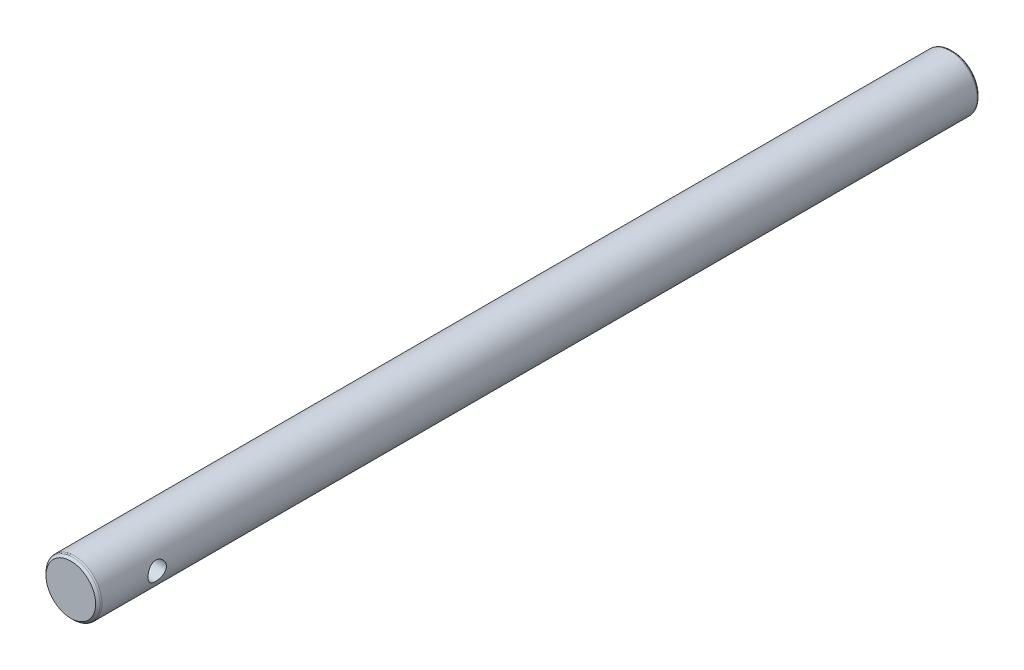
SolidWorks part; units mm, degrees
ref_plane "Front Plane" through (0, 0, 0) normal (0, 0, 1) x (1, 0, 0)
ref_plane "Top Plane" through (0, 0, 0) normal (0, 1, 0) x (1, 0, 0)
ref_plane "Right Plane" through (0, 0, 0) normal (1, 0, 0) x (0, 0, -1)
sketch "Sketch1" plane through (0, 0, 0) normal (0, 0, 1) x (1, 0, 0)
  line L0 (-4.7625, 0) -> (4.7625, 0) construction
  point P4 (0, 0)
  dimension "OD" = 9.525
sketch "Sketch2" plane through (0, 0, 0) normal (1, 0, 0) x (0, 0, -1)
  line L0 (152.4, 0) -> (-152.4, 0) construction
  line L1 (-152.4, 4.7625) -> (-152.4, -4.7625) construction
  line L2 (152.4, 4.7625) -> (152.4, -4.7625) construction
  point P0 (-141.4462, 0)
  point P4 (0, 0)
  point P6 (141.4462, 0)
  point P10 (152.4, 0)
  point P12 (-152.4, 0)
  dimension "Length" = 304.8
  dimension "D1" = 10.9537
  dimension "D2" = 10.9537
  dimension "D3" = 9.525
sketch "Sketch3" plane through (0, 0, 0) normal (0, 0, 1) x (1, 0, 0)
  circle A0 centre (0, 0) radius 4.7625
extrude "Boss-Extrude1" add sketch "Sketch3" along normal mid plane 152.4
chamfer "Chamfer1" distance 0.4763 angle 45 2 edges at (4.7625, 0, 76.2) (4.7625, 0, -76.2)
fillet "Fillet2" radius 0.3572 2 edges at (4.7625, 0, 75.7238) (4.7625, 0, -75.7237)
sketch "Sketch4" plane through (-4.7625, -167.656, -241.6273) normal (-1, 0, 0) x (0, 0, 1)
  line L0 (317.2031, 167.656) -> (-49682.7969, 167.656) construction
  line L1 (317.2031, 162.8935) -> (317.2031, 172.4185) construction
  line L2 (317.8273, 163.3698) -> (317.8273, 171.9423) construction
  circle A0 centre (307.6673, 167.656) radius 1.5875
  point P6 (317.2031, 167.656)
  point P7 (0, 0)
  dimension "D1" = 3.175
  dimension "D2" = 10.16
extrude "Cut-Extrude1" cut sketch "Sketch4" against normal through all
equation "\"D1@Boss-Extrude1\"=\"Length@Sketch2\""
equation "\"D1@Chamfer1\"=\"OD@Sketch1\"*.05"
equation "\"D1@Fillet2\"=\"D1@Chamfer1\"*.75"
equation "\"D3@Sketch2\"=\"OD@Sketch1\""
equation "\"D1@Sketch2\"=\"OD@Sketch1\"*1.15"
equation "\"D2@Sketch2\"=\"D1@Sketch2\""
